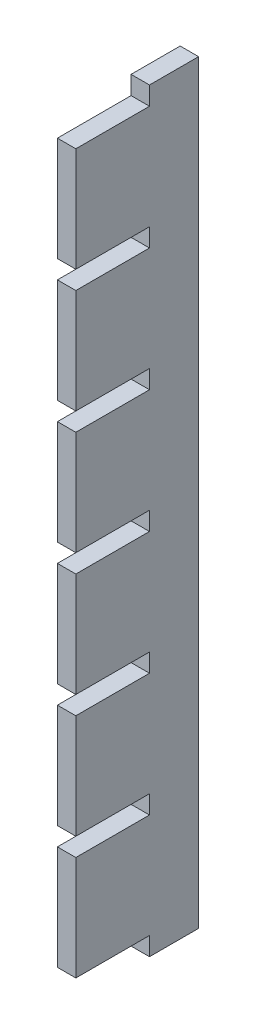
SolidWorks part; units mm, degrees
ref_plane "Front Plane" through (0, 0, 0) normal (0, 0, 1) x (1, 0, 0)
ref_plane "Top Plane" through (0, 0, 0) normal (0, 1, 0) x (1, 0, 0)
ref_plane "Right Plane" through (0, 0, 0) normal (1, 0, 0) x (0, 0, -1)
sketch "Sketch1" plane through (0, 0, 0) normal (1, 0, 0) x (0, 0, -1)
  line L1 (0, 0) -> (20, 0)
  line L2 (0, 0) -> (0, 123)
  line L3 (0, 123) -> (20, 123)
  line L4 (20, 0) -> (20, 123)
  dimension "D1" = 20
  dimension "D2" = 123
extrude "Boss-Extrude1" add sketch "Sketch1" along normal blind 3
sketch "Sketch2" plane through (3, 0, 0) normal (1, 0, 0) x (0, 0, -1)
  line L1 (0, 0) -> (12, 0)
  line L2 (0, 0) -> (0, 3)
  line L3 (0, 3) -> (12, 3)
  line L4 (12, 0) -> (12, 3)
  dimension "D1" = 12
  dimension "D2" = 3
extrude "Cut-Extrude1" cut sketch "Sketch2" against normal through all
pattern_linear "LPattern1" count 7 spacing 20 along (0, 1, 0) of "Cut-Extrude1"
